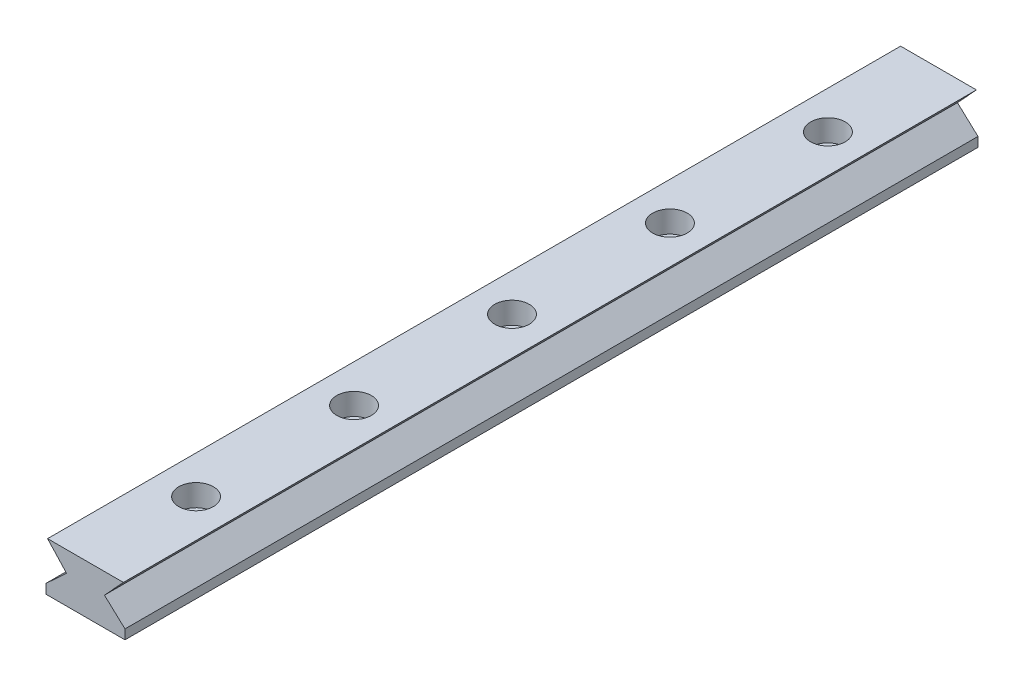
SolidWorks part; units mm, degrees
ref_plane "Front" through (0, 0, 0) normal (0, 0, 1) x (1, 0, 0)
ref_plane "Top" through (0, 0, 0) normal (0, 1, 0) x (1, 0, 0)
ref_plane "Right" through (0, 0, 0) normal (1, 0, 0) x (0, 0, -1)
sketch "Sketch1" plane through (0, 0, 0) normal (0, 0, 1) x (1, 0, 0)
  line L0 (-6.096, 7.874) -> (6.096, 7.874)
  line L1 (6.096, 7.874) -> (3.048, 4.572)
  line L2 (3.048, 4.572) -> (6.35, 1.524)
  line L3 (6.35, 1.524) -> (6.35, 0)
  line L4 (6.35, 0) -> (-6.35, 0)
  line L5 (-6.35, 0) -> (-6.35, 1.524)
  line L6 (-3.048, 4.572) -> (-6.096, 7.874)
  line L7 (-6.35, 1.524) -> (-3.048, 4.572)
  line L8 (-12.7, 14.3002) -> (12.7, 14.3002) construction
  line L9 (12.7, 14.3002) -> (12.7, 1.6002) construction
  line L10 (12.7, 1.6002) -> (6.2674, 1.6002) construction
  line L11 (-12.7, 1.6002) -> (-6.2675, 1.6002) construction
  line L12 (-12.7, 1.6002) -> (-12.7, 14.3002) construction
  point P7 (0, 7.874)
  dimension "Rail Offset (C)" = 1.524
  dimension "Rail Wd (A)" = 12.7
  dimension "Rail Ht (B)" = 7.874
  dimension "Rail Wd (D)" = 12.192
  dimension "Oall Ht (A)" = 14.3002
  dimension "Carriage Oall Wd (A)" = 25.4
  dimension "Carriage Ht (B)" = 12.7
extrude "Boss-Extrude1" add sketch "Sketch1" along normal mid plane 177.8
sketch "Sketch2" plane through (0, 0, 0) normal (1, 0, 0) x (0, 0, -1)
  line L0 (-78.9813, 7.874) -> (-78.9813, 4.3688)
  line L1 (-78.9813, 4.3688) -> (-77.9272, 4.3688)
  line L2 (-77.9272, 4.3688) -> (-77.9272, 0)
  line L3 (-77.9272, 0) -> (-76.2, 0)
  line L4 (-76.2, 0) -> (-76.2, 7.874)
  line L5 (-76.2, 7.874) -> (-78.9813, 7.874)
  line L6 (-88.9, 7.874) -> (88.9, 7.874) construction
  line L7 (-78.9813, 7.874) -> (-73.4187, 7.874) construction
  line L8 (-77.9272, 0) -> (-74.4728, 0) construction
  line L9 (-88.9, 0) -> (88.9, 0) construction
  line L10 (-88.9, 4.572) -> (-88.9, 7.874) construction
  dimension "H2" = 3.5052
  dimension "H1" = 5.5626
  dimension "H3" = 3.4544
  dimension "Hole Offset (E)" = 12.7
revolve "Cut-Revolve1" cut sketch "Sketch2" angle 360 mid plane about L4
pattern_linear "LPattern2" count 7 spacing 25.4 along (0, 0, -1) of "Cut-Revolve1"
sketch "Sketch3" plane through (0, 0, 0) normal (1, 0, 0) x (0, 0, -1)
  line L0 (-78.9813, 7.874) -> (-78.9813, 4.3688) construction
  line L1 (-78.9813, 4.3688) -> (-77.9272, 4.3688) construction
  line L2 (-77.9272, 4.3688) -> (-77.9272, 0) construction
  line L3 (-78.9813, 7.874) -> (-78.9813, 4.3688)
  line L4 (-78.9813, 4.3688) -> (-73.4187, 4.3688)
  line L5 (-77.9272, 4.3688) -> (-77.9272, 0)
  line L6 (-73.4187, 7.874) -> (-73.4187, 4.3688)
  line L7 (-88.9, 7.874) -> (88.9, 7.874) construction
  line L8 (-74.4728, 0) -> (-74.4728, 4.3688) construction
  line L9 (-74.4728, 4.3688) -> (-74.4728, 0)
  line L10 (-88.9, 0) -> (88.9, 0) construction
sketch "Sketch4" plane through (0, 7.874, 0) normal (0, 1, 0) x (1, 0, 0)
  line L3 (-9.2985, 68.58) -> (9.2985, 68.58)
  line L4 (-9.2985, 68.58) -> (-9.2985, 89.3444)
  line L5 (-9.2985, 89.3444) -> (9.2985, 89.3444)
  line L6 (9.2985, 68.58) -> (9.2985, 89.3444)
  line L7 (12.621, -68.58) -> (-12.621, -68.58)
  line L8 (12.621, -68.58) -> (12.621, -91.6184)
  line L9 (12.621, -91.6184) -> (-12.621, -91.6184)
  line L10 (-12.621, -68.58) -> (-12.621, -91.6184)
extrude "Cut-Extrude1" cut sketch "Sketch4" against normal through all
